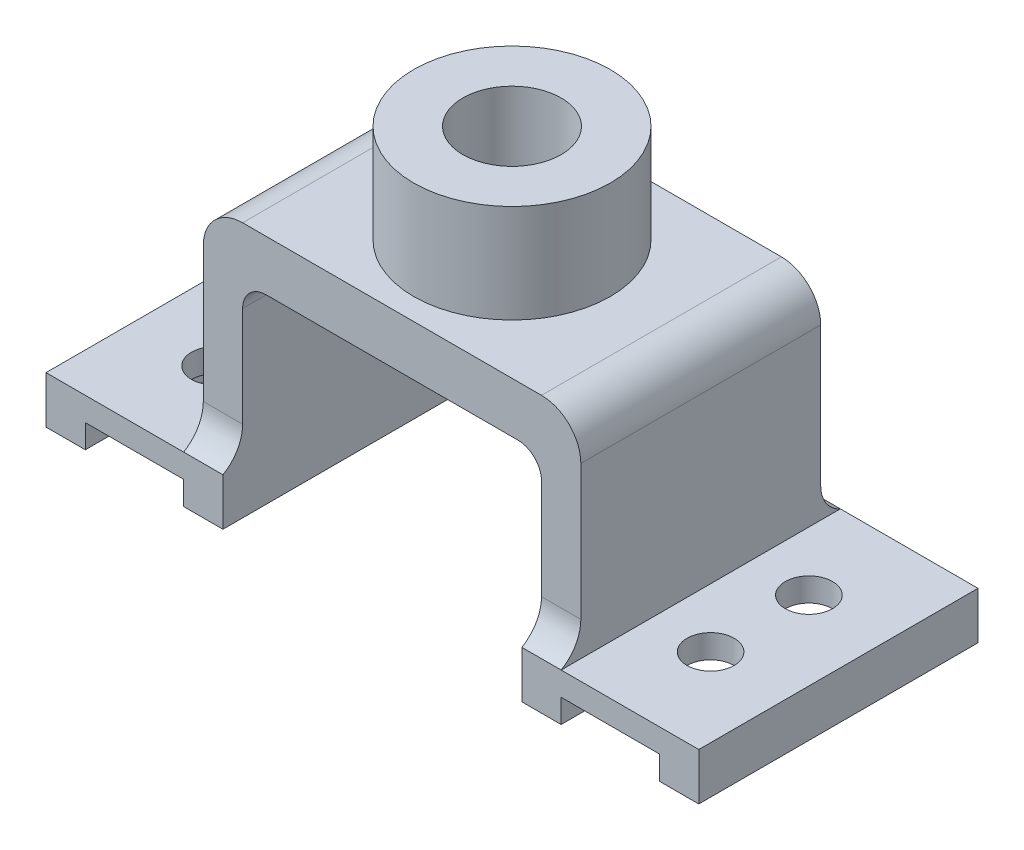
SolidWorks part; units mm, degrees
ref_plane "Front Plane" through (0, 0, 0) normal (0, 0, 1) x (1, 0, 0)
ref_plane "Top Plane" through (0, 0, 0) normal (0, 1, 0) x (1, 0, 0)
ref_plane "Right Plane" through (0, 0, 0) normal (1, 0, 0) x (0, 0, -1)
sketch "Sketch1" plane through (0, 0, 0) normal (0, 1, 0) x (1, 0, 0)
  line L1 (0, 0) -> (166, 0)
  line L2 (0, 0) -> (0, 71)
  line L3 (0, 71) -> (166, 71)
  line L4 (166, 0) -> (166, 71)
  dimension "D1" = 166
  dimension "D2" = 71
extrude "Boss-Extrude1" add sketch "Sketch1" along normal blind 12
sketch "Sketch2" plane through (0, 12, 0) normal (0, 1, 0) x (1, 0, 0)
  line L0 (166, 71) -> (0, 71) construction
  line L1 (0, 71) -> (0, 0) construction
  circle A0 centre (20, 48) radius 6
  circle A1 centre (20, 23) radius 6
  circle A2 centre (146, 48) radius 6
  circle A3 centre (146, 23) radius 6
  dimension "D1" = 12
  dimension "D2" = 12
  dimension "D3" = 12
  dimension "D4" = 12
  dimension "D5" = 25
  dimension "D6" = 23
  dimension "D7" = 126
  dimension "D8" = 20
extrude "Cut-Extrude1" cut sketch "Sketch2" against normal through all
sketch "Sketch3" plane through (0, 12, 0) normal (0, 1, 0) x (1, 0, 0)
  line L0 (166, 71) -> (0, 71) construction
  line L1 (35, 71) -> (131, 71)
  line L2 (35, 71) -> (35, 0)
  line L3 (35, 0) -> (131, 0)
  line L4 (131, 71) -> (131, 0)
  line L5 (0, 0) -> (166, 0) construction
  line L6 (0, 71) -> (0, 0) construction
  dimension "D1" = 96
  dimension "D2" = 35
extrude "Boss-Extrude2" add sketch "Sketch3" along normal blind 53
sketch "Sketch4" plane through (0, 0, 0) normal (0, 0, 1) x (1, 0, 0)
  line L0 (0, 0) -> (166, 0) construction
  line L1 (45, 0) -> (121, 0)
  line L2 (45, 0) -> (45, 46.1355)
  line L3 (51, 52.1355) -> (115, 52.1355)
  line L4 (121, 0) -> (121, 46.1355)
  line L5 (131, 65) -> (131, 12) construction
  line L7 (0, 12) -> (0, 0) construction
  line L8 (10, 0) -> (35, 0)
  line L9 (10, 0) -> (10, 6)
  line L10 (10, 6) -> (35, 6)
  line L11 (35, 0) -> (35, 6)
  line L12 (131, 0) -> (156, 0)
  line L13 (131, 0) -> (131, 6)
  line L14 (131, 6) -> (156, 6)
  line L15 (156, 0) -> (156, 6)
  line L16 (166, 12) -> (166, 0) construction
  arc A0 (121, 46.1355) -> (115, 52.1355) centre (115, 46.1355) ccw
  arc A1 (45, 46.1355) -> (51, 52.1355) centre (51, 46.1355) cw
  point P22 (121, 52.1355)
  point P25 (45, 52.1355)
  dimension "D9" = 6
  dimension "D1" = 76
  dimension "D2" = 10
  dimension "D3" = 6
  dimension "D4" = 10
  dimension "D5" = 10
  dimension "D6" = 10
  dimension "D7" = 10
  dimension "D8" = 6
extrude "Cut-Extrude2" cut sketch "Sketch4" against normal through all
sketch "Sketch5" plane through (35, 0, 0) normal (-1, 0, 0) x (0, 0, 1)
  line L0 (-71, 65) -> (0, 65) construction
  line L1 (-66, 65) -> (-71, 65)
  line L2 (-66, 65) -> (-66, 12)
  line L3 (-66, 12) -> (-71, 12)
  line L4 (-71, 65) -> (-71, 12)
  line L6 (-5, 65) -> (0, 65)
  line L7 (-5, 65) -> (-5, 12)
  line L8 (-5, 12) -> (0, 12)
  line L9 (0, 65) -> (0, 12)
  dimension "D1" = 5
  dimension "D2" = 5
extrude "Cut-Extrude4" cut sketch "Sketch5" against normal through all
ref_plane "Plane2" through (35, 0, 0) normal (-1, 0, 0) x (0, 0, 1)
sketch "Sketch7" plane through (35, 0, 0) normal (-1, 0, 0) x (0, 0, 1)
  line L0 (-71, 12) -> (-66, 12)
  line L1 (-66, 12) -> (-66, 19.6101)
  line L2 (-66, 12) -> (-66, 65) construction
  line L3 (-5, 20.6603) -> (-5, 12)
  line L4 (-5, 65) -> (-5, 12) construction
  line L5 (-5, 12) -> (0, 12)
  arc A0 (-66, 19.6101) -> (-71, 12) centre (-74.2914, 19.6101) cw
  arc A1 (-5, 20.6603) -> (0, 12) centre (5, 20.6603) ccw
  dimension "D1" = 10
extrude "Boss-Extrude4" add sketch "Sketch7" against normal up to surface (10 mm away) up to face at (45, 17.5339, -35.5)
ref_plane "Plane3" through (131, 0, 0) normal (1, 0, 0) x (0, 0, -1)
sketch "Sketch10" plane through (131, 0, 0) normal (1, 0, 0) x (0, 0, -1)
  line L0 (5, 20.6603) -> (5, 12)
  line L1 (5, 12) -> (0, 12)
  line L2 (71, 12) -> (66, 12)
  line L3 (66, 12) -> (66, 19.6101)
  arc A0 (5, 20.6603) -> (0, 12) centre (-5, 20.6603) cw
  arc A1 (66, 19.6101) -> (71, 12) centre (74.2914, 19.6101) ccw
extrude "Boss-Extrude5" add sketch "Sketch10" against normal up to surface (10 mm away) up to face at (121, 17.5339, -35.5)
fillet "Fillet4" radius 10 1 edges at (35, 65, -35.5)
fillet "Fillet5" radius 10 1 edges at (131, 65, -35.5)
sketch "Sketch11" plane through (0, 65, 0) normal (0, 1, 0) x (1, 0, 0)
  circle A0 centre (83, 35.5) radius 25
  circle A1 centre (83, 35.5) radius 12.5
  dimension "D1" = 25
  dimension "D2" = 50
extrude "Boss-Extrude6" add sketch "Sketch11" along normal blind 25
sketch "Sketch12" plane through (0, 65, 0) normal (0, 1, 0) x (1, 0, 0)
  circle A0 centre (83, 35.5) radius 12.5
extrude "Cut-Extrude5" cut sketch "Sketch12" against normal through all
